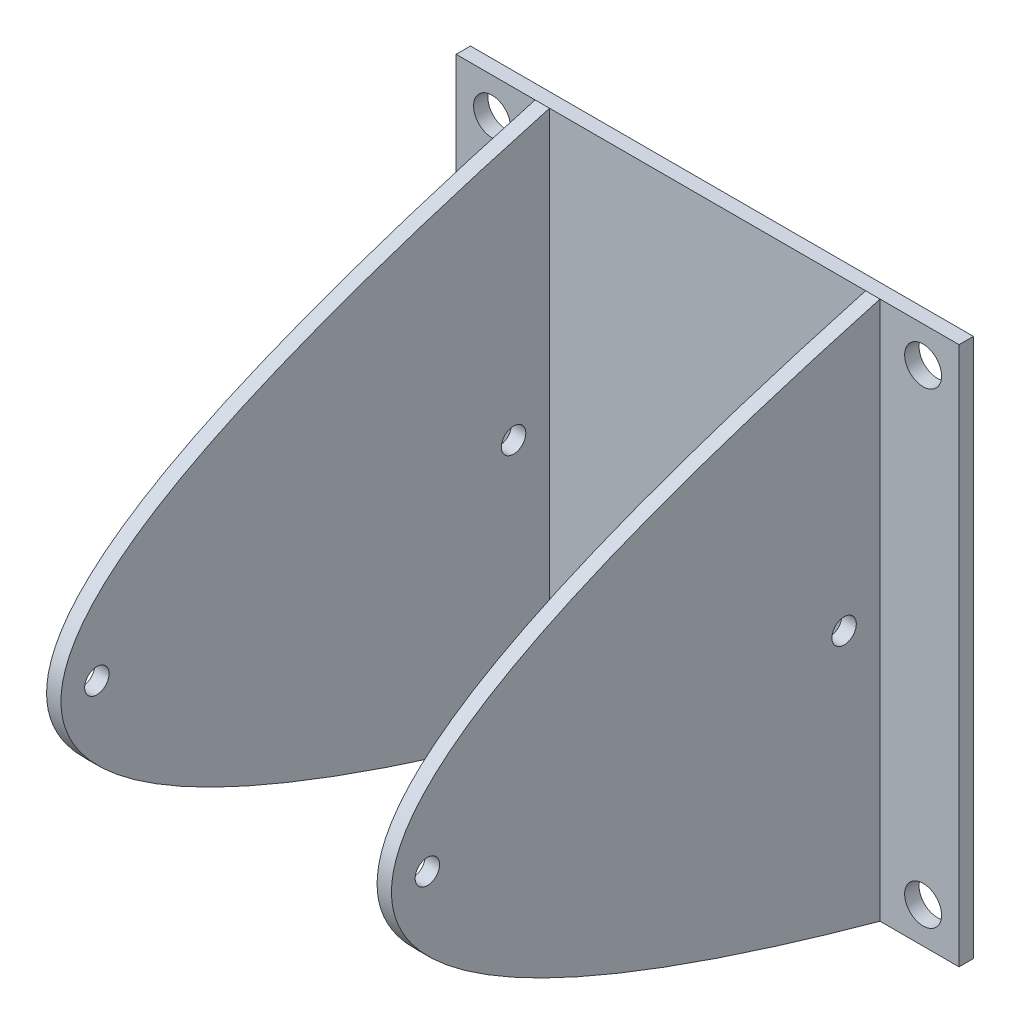
SolidWorks part; units mm, degrees
material "6061 Alloy"
ref_plane "Front Plane" through (0, 0, 0) normal (0, 0, 1) x (1, 0, 0)
ref_plane "Top Plane" through (0, 0, 0) normal (0, 1, 0) x (1, 0, 0)
ref_plane "Right Plane" through (0, 0, 0) normal (1, 0, 0) x (0, 0, -1)
sketch "Sketch1" plane through (0, 0, 0) normal (0, 0, 1) x (1, 0, 0)
  line L1 (-44.45, 47.625) -> (44.45, 47.625)
  line L2 (-44.45, 47.625) -> (-44.45, -47.625)
  line L3 (-44.45, -47.625) -> (44.45, -47.625)
  line L4 (44.45, 47.625) -> (44.45, -47.625)
  line L5 (-44.45, 47.625) -> (44.45, -47.625) construction
  line L6 (-44.45, -47.625) -> (44.45, 47.625) construction
  circle A0 centre (-38.1, -41.275) radius 3.2639
  circle A1 centre (38.1, -41.275) radius 3.2639
  circle A2 centre (38.1, 41.275) radius 3.2639
  circle A3 centre (-38.1, 41.275) radius 3.2639
  point P0 (0, 0)
  dimension "D1" = 95.25
  dimension "D4" = 6.35
  dimension "D3" = 82.55
  dimension "D2" = 88.9
  dimension "D5" = 6.35
  dimension "D6" = 82.55
extrude "Boss-Extrude1" add sketch "Sketch1" along normal blind 2.54
ref_plane "Plane1" through (30.48, 0, 0) normal (1, 0, 0) x (0, 0, -1)
sketch "Sketch4" plane through (30.48, 0, 0) normal (1, 0, 0) x (0, 0, -1)
  line L5 (0, -47.625) -> (0, 47.625)
  line L6 (0, 47.625) -> (-2.54, 47.625)
  line L7 (-2.54, 47.625) -> (-2.54, -47.625)
  line L8 (-2.54, -47.625) -> (0, -47.625)
  line L11 (-2.54, 47.625) -> (-2.54, -47.625)
  circle A0 centre (-82.55, 0) radius 2.159
  circle A1 centre (-8.89, 0) radius 2.159
  spline S0 degree 2 poles (-2.54, 47.625) (-175.26, 0) (-2.54, -47.625) knots 0 0 0 1 1 1
  point P6 (-85.2727, 0)
  point P7 (0, 0)
  dimension "D2" = 6.35
  dimension "D3" = 6.35
  dimension "D1" = 0
extrude "Boss-Extrude2" add sketch "Sketch4" against normal blind 2.54
mirror "Mirror1" about plane through (0, 0, 0) normal (1, 0, 0) of "Boss-Extrude2"
